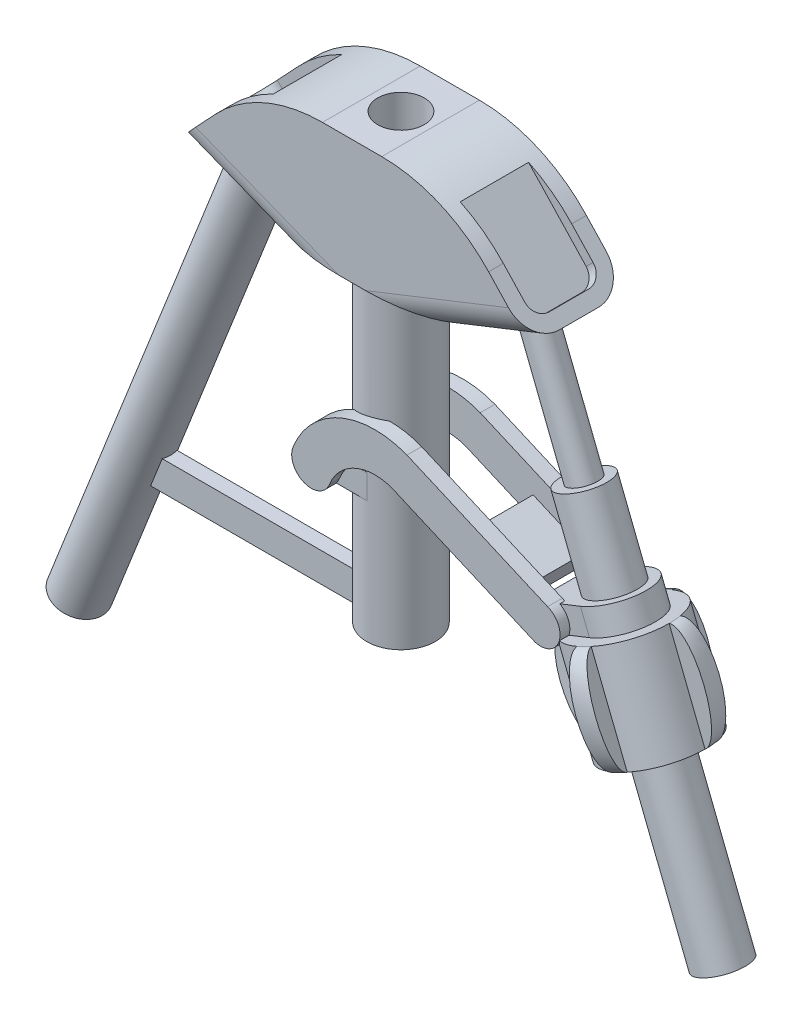
SolidWorks part; units mm, degrees
ref_plane "Front Plane" through (0, 0, 0) normal (0, 0, 1) x (1, 0, 0)
ref_plane "Top Plane" through (0, 0, 0) normal (0, 1, 0) x (1, 0, 0)
ref_plane "Right Plane" through (0, 0, 0) normal (1, 0, 0) x (0, 0, -1)
sketch "Sketch1" plane through (0, 0, 0) normal (0, 0, 1) x (1, 0, 0)
  line L0 (0, -8.362) -> (38.1, -8.362)
  line L1 (38.1, -8.362) -> (55.4742, -26.8856)
  line L2 (55.4742, -26.8856) -> (38.1, -33.762)
  line L3 (19.05, -8.362) -> (19.05, -33.762) construction
  line L4 (38.1, -33.762) -> (0, -33.762)
  line L5 (-17.3742, -26.8856) -> (0, -33.762)
  line L6 (0, -8.362) -> (-17.3742, -26.8856)
  dimension "D1" = 38.1
  dimension "D2" = 25.4
extrude "Boss-Extrude2" add sketch "Sketch1" along normal blind 20
fillet "Fillet1" radius 30 2 edges at (0, -8.362, 10) (38.1, -8.362, 10)
fillet "Fillet2" radius 6 4 edges at (-8.6871, -30.3238, 0) (-8.6871, -30.3238, 20) (46.7871, -30.3238, 0) (46.7871, -30.3238, 20)
sketch "Sketch2" plane through (0, -33.762, 0) normal (0, -1, 0) x (1, 0, 0)
  circle A0 centre (19.05, 10) radius 7
  dimension "D1" = 14
extrude "Boss-Extrude3" add sketch "Sketch2" along normal blind 65.09
sketch "Sketch3" plane through (0, -98.8519, 0) normal (0, -1, 0) x (1, 0, 0)
  circle A0 centre (19.05, 10) radius 4.7625
extrude "Cut-Extrude1" cut sketch "Sketch3" against normal through all
sketch "Sketch6" plane through (16.7126, -42.2267, 0) normal (0.368, -0.9298, 0) x (-0.9298, -0.368, 0)
  circle A0 centre (-32.3443, -10) radius 3
  dimension "D1" = 6
extrude "Boss-Extrude5" add sketch "Sketch6" along normal blind 26.4398 and the other way blind 2
sketch "Sketch8" plane through (26.4426, -66.8111, 0) normal (0.368, -0.9298, 0) x (0.9298, 0.368, 0)
  circle A0 centre (32.3443, 10) radius 5
  dimension "D1" = 10
extrude "Boss-Extrude6" add sketch "Sketch8" along normal blind 77
sketch "Sketch9" plane through (-11.5527, -29.1896, 0) normal (-0.368, -0.9298, 0) x (-0.9298, 0.368, 0)
  circle A0 centre (-3.0819, -10) radius 5
  dimension "D1" = 10
extrude "Boss-Extrude7" add sketch "Sketch9" along normal blind 103.4
ref_plane "Plane2" through (32.6987, -82.6181, 0) normal (0.368, -0.9298, 0) x (-0.9298, -0.368, 0)
sketch "Sketch11" plane through (32.6987, -82.6181, 0) normal (0.368, -0.9298, 0) x (-0.9298, -0.368, 0)
  line L0 (-32.3443, -3) -> (-22.2599, -3)
  line L1 (-22.2599, -3) -> (-22.2599, -17)
  line L2 (-22.2599, -17) -> (-32.3443, -17)
  arc A0 (-32.3443, -3) -> (-32.3443, -17) centre (-32.3443, -10) ccw
  dimension "D1" = 7
extrude "Boss-Extrude8" add sketch "Sketch11" along normal blind 5
ref_plane "Plane3" through (0, -68.8519, 0) normal (0, -1, 0) x (-1, 0, 0)
sketch "Sketch15" plane through (0, -68.8519, 0) normal (0, -1, 0) x (-1, 0, 0)
  line L0 (-19.05, -3) -> (-7.1858, -3)
  line L1 (-7.1858, -3) -> (-7.1858, -17)
  line L2 (-7.1858, -17) -> (-19.05, -17)
  arc A0 (-19.05, -3) -> (-19.05, -17) centre (-19.05, -10) ccw
  dimension "D1" = 7
extrude "Boss-Extrude9" add sketch "Sketch15" along normal blind 5
sketch "Sketch17" plane through (16.0963, 15.0975, 0) normal (0.7294, 0.6841, 0) x (0, 0, -1)
  line L0 (-17, -51.5604) -> (-17, -29.5604)
  line L2 (-17, -29.5604) -> (-3, -29.5604)
  line L3 (-3, -29.5604) -> (-3, -51.5604)
  line L7 (-6, -54.5604) -> (-14, -54.5604)
  arc A0 (-3, -51.5604) -> (-6, -54.5604) centre (-6, -51.5604) cw
  arc A1 (-14, -54.5604) -> (-17, -51.5604) centre (-14, -51.5604) cw
  dimension "D1" = 3
extrude "Cut-Extrude2" cut sketch "Sketch17" against normal blind 2
ref_plane "Plane5" through (19.05, -8.362, 20) normal (-1, 0, 0) x (0, 0, 1)
mirror "Mirror2" about plane through (19.05, -8.362, 20) normal (-1, 0, 0) of "Cut-Extrude2"
ref_plane "Plane6" through (0, 0, 10) normal (0, 0, 1) x (1, 0, 0)
sketch "Sketch19" plane through (0, 0, 17) normal (0, 0, 1) x (1, 0, 0)
  line L3 (58.0571, -72.1458) -> (29.2722, -59.674)
  line L4 (55.4597, -79.7058) -> (26.3635, -67.1265)
  arc A0 (5.9596, -69.8976) -> (13.4121, -72.8063) centre (9.6858, -71.3519) ccw
  arc A1 (55.4597, -79.7058) -> (58.0571, -72.1458) centre (56.6083, -75.8742) ccw
  arc A2 (29.2722, -59.674) -> (5.9596, -69.8976) centre (22.7277, -76.4421) ccw
  arc A3 (26.3635, -67.1265) -> (13.4121, -72.8063) centre (22.7277, -76.4421) ccw
  dimension "D1" = 4
  dimension "D2" = 4
extrude "Boss-Extrude14" add sketch "Sketch19" along normal blind 2 and the other way blind 1
mirror "Mirror4" about plane through (0, 0, 10) normal (0, 0, 1) of "Boss-Extrude14"
sketch "Sketch20" plane through (0, 0, 19) normal (0, 0, 1) x (1, 0, 0)
  line L0 (49.4192, -77.0942) -> (38.5429, -72.3921)
  line L1 (26.3635, -67.1265) -> (55.4597, -79.7058) construction
  line L2 (38.5429, -72.3921) -> (40.0893, -68.8152)
  line L3 (40.0893, -68.8152) -> (50.9655, -73.5174)
  line L4 (50.9655, -73.5174) -> (49.4192, -77.0942)
extrude "Boss-Extrude15" add sketch "Sketch20" against normal up to surface (15 mm away) up to face at (44.2752, -70.6972, 4)
ref_axis "Axis1" through (82.1125, -119.5786, 10) along (-0.368, 0.9298, 0)
sketch "Sketch22" plane through (0, 0, 10) normal (0, 0, 1) x (1, 0, 0)
  line L0 (64.6133, -75.3643) -> (73.9115, -71.6842)
  line L1 (59.9641, -77.2043) -> (69.2624, -73.5242) construction
  line L2 (71.9734, -93.9607) -> (81.2716, -90.2806)
  line L3 (82.1125, -119.5786) -> (67.3544, -82.2901) construction
  line L4 (71.9734, -93.9607) -> (64.6133, -75.3643)
  ellipse E0 centre (77.3796, -81.0959) end of major axis (73.9115, -71.6842) minor radius 4.1479 (81.2716, -90.2806) -> (73.9115, -71.6842) ccw
  dimension "D1" = 10
  dimension "D2" = 20
  dimension "D3" = 10
sketch "Sketch23" plane through (34.5387, -87.2672, 0) normal (0.368, -0.9298, 0) x (0.9298, 0.368, 0)
  circle A0 centre (32.3443, 10) radius 10
extrude "Boss-Extrude17" add sketch "Sketch23" along normal blind 20
revolve "Revolve1" add sketch "Sketch22" angle 15 about axis through (82.1125, -119.5786, 10) along (-0.368, 0.9298, 0)
pattern_circular "CirPattern1" count 4 every 91 about axis through (82.1125, -119.5786, 10) along (-0.368, 0.9298, 0) of "Revolve1"
sketch "Sketch24" plane through (-49.6046, -125.3334, 0) normal (-0.368, -0.9298, 0) x (0.9298, -0.368, 0)
  circle A0 centre (3.0819, 10) radius 3.175
extrude "Cut-Extrude3" cut sketch "Sketch24" against normal blind 25.4
sketch "Sketch25" plane through (54.7791, -138.4075, 0) normal (0.368, -0.9298, 0) x (0.9298, 0.368, 0)
  circle A0 centre (32.3443, 10) radius 3.175
extrude "Cut-Extrude4" cut sketch "Sketch25" against normal blind 25.4
sketch "Sketch26" plane through (0, 0, 10) normal (0, 0, 1) x (1, 0, 0)
  line L1 (13.2412, -98.8519) -> (-33.7382, -98.8519)
  line L2 (13.2412, -98.8519) -> (13.2412, -92.8519)
  line L3 (13.2412, -92.8519) -> (-33.7382, -92.8519)
  line L4 (-33.7382, -98.8519) -> (-33.7382, -92.8519)
  dimension "D1" = 6
extrude "Boss-Extrude20" add sketch "Sketch26" along normal blind 1.5 and the other way blind 1.5
